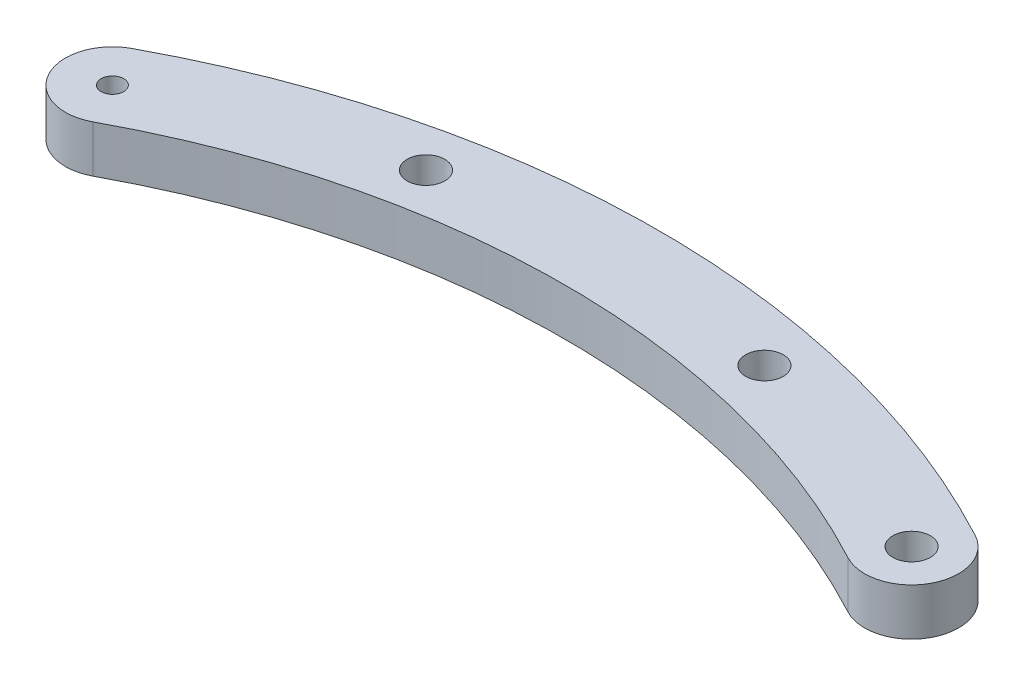
SolidWorks part; units mm, degrees
ref_plane "Front Plane" through (0, 0, 0) normal (0, 0, 1) x (1, 0, 0)
ref_plane "Top Plane" through (0, 0, 0) normal (0, 1, 0) x (1, 0, 0)
ref_plane "Right Plane" through (0, 0, 0) normal (1, 0, 0) x (0, 0, -1)
sketch "Sketch1" plane through (0, 0, 0) normal (0, 1, 0) x (1, 0, 0)
  circle A0 centre (0, 0) radius 2.5
  circle A1 centre (42.5, 0) radius 2.5
  arc A2 (0, 0) -> (42.5, 0) centre (21.25, -39.6666) cw construction
  arc A3 (1.1806, -2.2037) -> (41.3194, -2.2037) centre (21.25, -39.6666) cw
  arc A4 (-1.1806, 2.2037) -> (43.6806, 2.2037) centre (21.25, -39.6666) cw
  circle A5 centre (0, 0) radius 0.6
  circle A6 centre (42.5, 0) radius 1
  dimension "D1" = 45
  dimension "D5" = 1.2
  dimension "D6" = 2
  dimension "D4" = 42.5
  dimension "D2" = 2.5
  dimension "D3" = 2.5
extrude "Boss-Extrude1" add sketch "Sketch1" along normal blind 2.5 contours A0 A5 | A4 A0 A3 A1 | A1 A6
sketch "Sketch2" plane through (0, 2.5, 0) normal (0, 1, 0) x (1, 0, 0)
  arc A0 (0, 0) -> (42.5, 0) centre (21.25, -39.6666) cw construction
  circle A1 centre (12.25, 4.4242) radius 1
  circle A2 centre (30.25, 4.4242) radius 1
  dimension "D1" = 45
  dimension "D2" = 18
  dimension "D3" = 2
extrude "Cut-Extrude1" cut sketch "Sketch2" against normal through all
